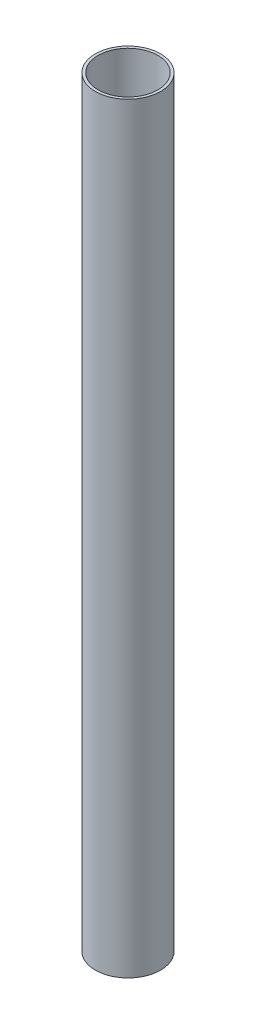
SolidWorks part; units mm, degrees
ref_plane "Front Plane" through (0, 0, 0) normal (0, 0, 1) x (1, 0, 0)
ref_plane "Top Plane" through (0, 0, 0) normal (0, 1, 0) x (1, 0, 0)
ref_plane "Right Plane" through (0, 0, 0) normal (1, 0, 0) x (0, 0, -1)
sketch "Sketch1" plane through (0, 0, 0) normal (0, 1, 0) x (1, 0, 0)
  circle A0 centre (0, 0) radius 6
  circle A1 centre (0, 0) radius 5.5
  dimension "D1" = 12
  dimension "D2" = 11
extrude "Boss-Extrude1" add sketch "Sketch1" along normal blind 140
